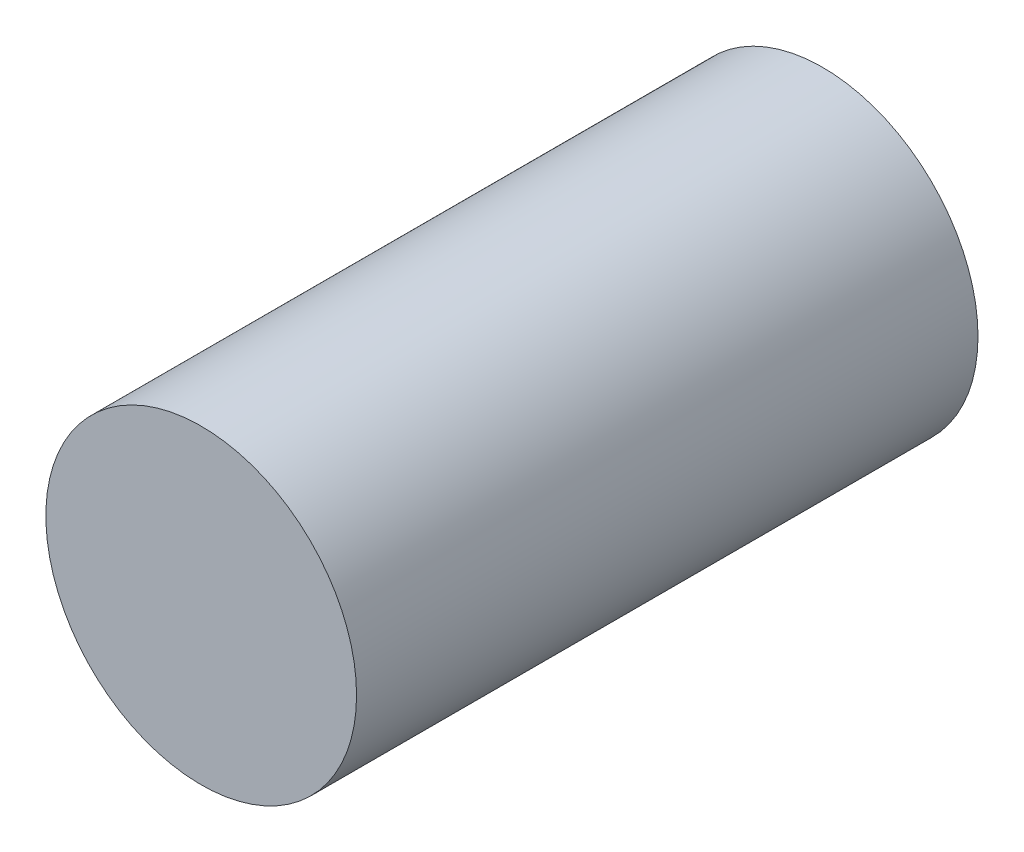
SolidWorks part; units mm, degrees
ref_plane "Front Plane" through (0, 0, 0) normal (0, 0, 1) x (1, 0, 0)
ref_plane "Top Plane" through (0, 0, 0) normal (0, 1, 0) x (1, 0, 0)
ref_plane "Right Plane" through (0, 0, 0) normal (1, 0, 0) x (0, 0, -1)
sketch "Sketch1" plane through (0, 0, 0) normal (0, 0, 1) x (1, 0, 0)
  circle A0 centre (0, 0) radius 7.5
  dimension "D1" = 15
extrude "Boss-Extrude1" add sketch "Sketch1" against normal blind 30
